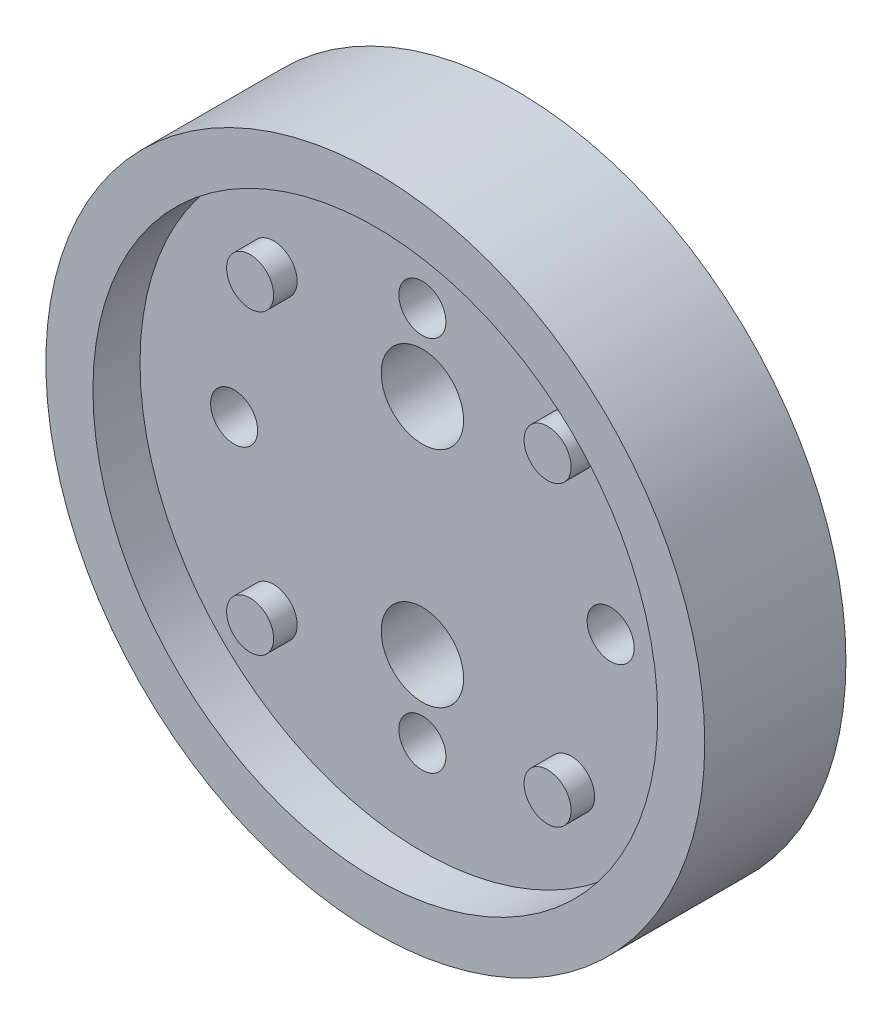
SolidWorks part; units mm, degrees
ref_plane "Front Plane" through (0, 0, 0) normal (0, 0, 1) x (1, 0, 0)
ref_plane "Top Plane" through (0, 0, 0) normal (0, 1, 0) x (1, 0, 0)
ref_plane "Right Plane" through (0, 0, 0) normal (1, 0, 0) x (0, 0, -1)
sketch "Sketch1" plane through (0, 0, 0) normal (0, 0, 1) x (1, 0, 0)
  circle A0 centre (0, 0) radius 14
  dimension "D1" = 28
extrude "Boss-Extrude1" add sketch "Sketch1" along normal blind 4
sketch "Sketch2" plane through (0, 0, 4) normal (0, 0, 1) x (1, 0, 0)
  circle A0 centre (0, 0) radius 14
  circle A1 centre (0, 0) radius 12
  circle A2 centre (0, 0) radius 14 construction
  dimension "D1" = 2
extrude "Boss-Extrude2" add sketch "Sketch2" along normal blind 2
sketch "Sketch3" plane through (0, 0, 4) normal (0, 0, 1) x (1, 0, 0)
  line L0 (0, 12) -> (0, -12) construction
  line L1 (12, 0) -> (-12, 0) construction
  line L2 (0.8321, 9) -> (-1.8969, 9) construction
  line L3 (0, 12) -> (-3.3981, 12) construction
  circle A0 centre (0, 0) radius 12 construction
  circle A1 centre (0, 8) radius 1
  circle A2 centre (8, 0) radius 1
  circle A3 centre (0, -8) radius 1
  circle A4 centre (-8, 0) radius 1
  dimension "D1" = 2
  dimension "D2" = 3
  dimension "D3" = 4
extrude "Cut-Extrude1" cut sketch "Sketch3" against normal through all
sketch "Sketch4" plane through (0, 0, 4) normal (0, 0, 1) x (1, 0, 0)
  line L0 (0, 3) -> (0, 0) construction
  line L1 (0, 0) -> (0, -3) construction
  circle A0 centre (0, 4.75) radius 1.75
  circle A1 centre (0, -4.75) radius 1.75
  dimension "D1" = 3.5
  dimension "D2" = 3
extrude "Cut-Extrude2" cut sketch "Sketch4" against normal through all
sketch "Sketch5" plane through (0, 0, 4) normal (0, 0, 1) x (1, 0, 0)
  line L0 (0, 0) -> (-8.4853, -8.4853) construction
  line L1 (0, 0) -> (-12, 0) construction
  circle A0 centre (0, 0) radius 12 construction
  circle A1 centre (0, 0) radius 12 construction
  circle A2 centre (-6.3208, -6.3208) radius 1
  circle A3 centre (-6.3208, 6.3208) radius 1
  circle A4 centre (6.3208, 6.3208) radius 1
  circle A5 centre (6.3208, -6.3208) radius 1
  dimension "D2" = 4
  dimension "D1" = 45
extrude "Boss-Extrude3" add sketch "Sketch5" along normal blind 1
